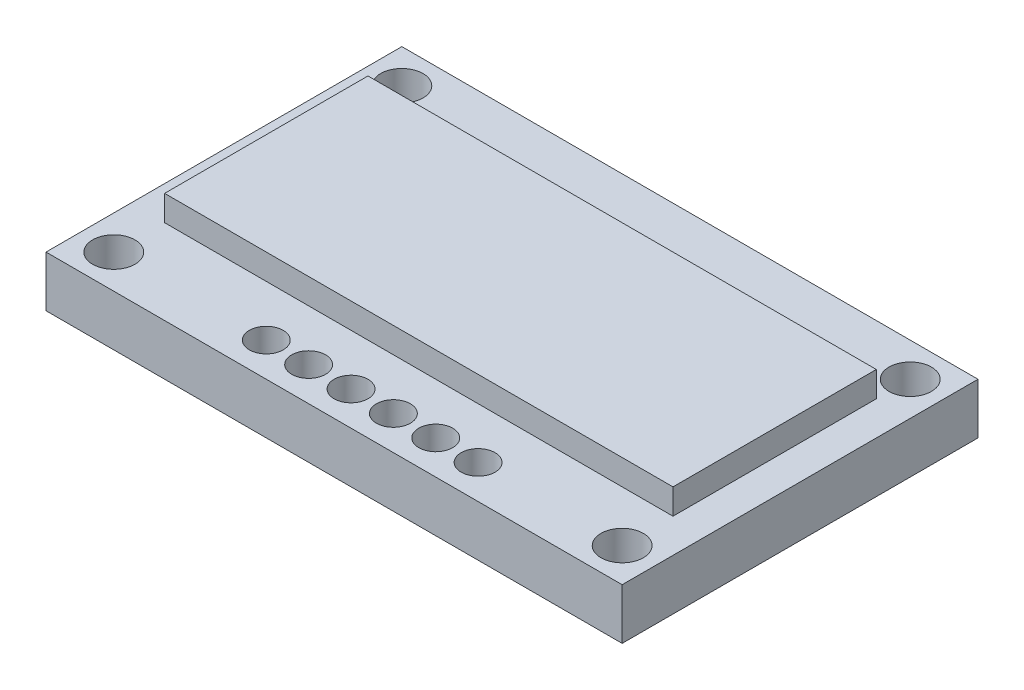
SolidWorks part; units mm, degrees
ref_plane "Plan de face" through (0, 0, 0) normal (0, 0, 1) x (1, 0, 0)
ref_plane "Plan de dessus" through (0, 0, 0) normal (0, 1, 0) x (1, 0, 0)
ref_plane "Plan de droite" through (0, 0, 0) normal (1, 0, 0) x (0, 0, -1)
sketch "Esquisse1" plane through (0, 0, 0) normal (0, 1, 0) x (1, 0, 0)
  line L1 (0, 0) -> (34, 0)
  line L2 (0, 0) -> (0, 21)
  line L3 (0, 21) -> (34, 21)
  line L4 (34, 0) -> (34, 21)
  dimension "D1" = 34
  dimension "D2" = 21
extrude "Boss.-Extru.1" add sketch "Esquisse1" along normal blind 3
sketch "Esquisse2" plane through (0, 3, 0) normal (0, 1, 0) x (1, 0, 0)
  line L0 (34, 21) -> (0, 21) construction
  line L1 (2, 17) -> (32, 17)
  line L2 (2, 17) -> (2, 5)
  line L3 (2, 5) -> (32, 5)
  line L4 (32, 17) -> (32, 5)
  line L5 (0, 21) -> (0, 0) construction
  dimension "D1" = 30
  dimension "D2" = 12
  dimension "D3" = 4
  dimension "D4" = 2
extrude "Boss.-Extru.2" add sketch "Esquisse2" along normal blind 1.5
sketch "Esquisse3" plane through (0, 3, 0) normal (0, 1, 0) x (1, 0, 0)
  line L0 (0, 21) -> (0, 0) construction
  line L2 (0, 0) -> (34, 0) construction
  line L3 (34, 21) -> (0, 21) construction
  line L4 (34, 0) -> (34, 21) construction
  circle A0 centre (11, 2) radius 1
  circle A1 centre (13.5, 2) radius 1
  circle A2 centre (16, 2) radius 1
  circle A3 centre (18.5, 2) radius 1
  circle A4 centre (21, 2) radius 1
  circle A5 centre (23.5, 2) radius 1
  circle A6 centre (2, 2) radius 1.25
  circle A7 centre (2, 19) radius 1.25
  circle A8 centre (32, 19) radius 1.25
  circle A9 centre (32, 2) radius 1.25
  dimension "D1" = 2
  dimension "D2" = 2
  dimension "D3" = 2
  dimension "D4" = 2
  dimension "D5" = 2
  dimension "D6" = 2
  dimension "D7" = 11
  dimension "D8" = 2.5
  dimension "D9" = 2.5
  dimension "D10" = 2.5
  dimension "D11" = 2.5
  dimension "D12" = 2.5
  dimension "D13" = 2
  dimension "D14" = 2
  dimension "D15" = 2
  dimension "D16" = 2
  dimension "D17" = 2
  dimension "D18" = 2
  dimension "D19" = 2.5
  dimension "D20" = 2.5
  dimension "D21" = 2.5
  dimension "D22" = 2.5
  dimension "D23" = 2
  dimension "D24" = 2
  dimension "D25" = 2
  dimension "D26" = 2
  dimension "D27" = 2
  dimension "D28" = 2
  dimension "D29" = 2
  dimension "D30" = 2
extrude "Enlèv. mat.-Extru.1" cut sketch "Esquisse3" against normal blind 5
